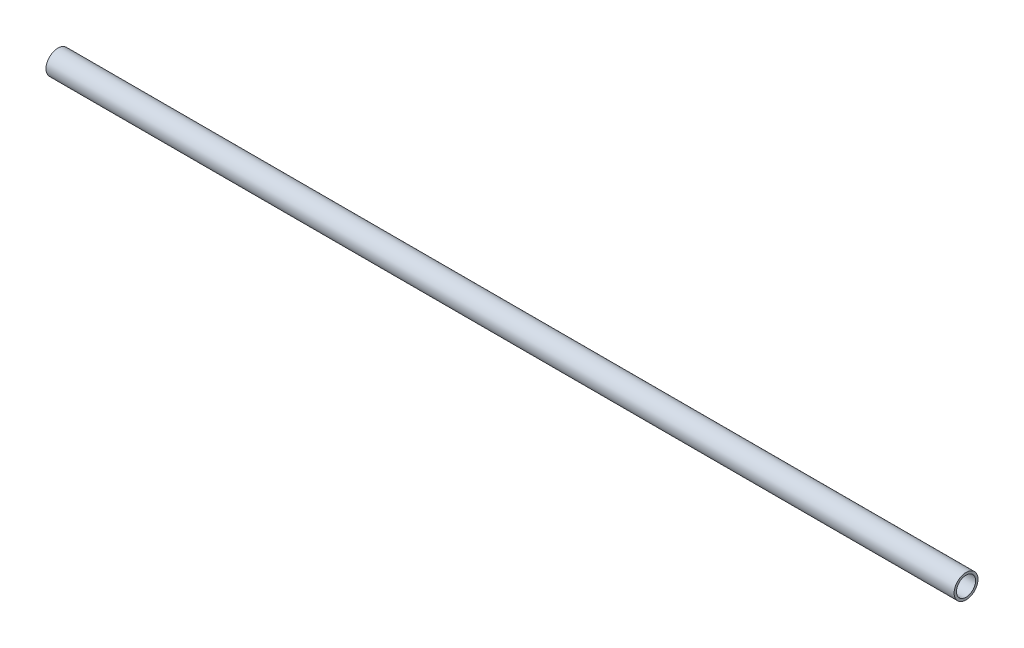
SolidWorks part; units mm, degrees
ref_plane "Front Plane" through (0, 0, 0) normal (0, 0, 1) x (1, 0, 0)
ref_plane "Top Plane" through (0, 0, 0) normal (0, 1, 0) x (1, 0, 0)
ref_plane "Right Plane" through (0, 0, 0) normal (1, 0, 0) x (0, 0, -1)
sketch "Sketch1" plane through (0, 0, 0) normal (1, 0, 0) x (0, 0, -1)
  circle A0 centre (0, 0) radius 2.5
  circle A1 centre (0, 0) radius 2
  dimension "D1" = 5
  dimension "D2" = 4
extrude "Boss-Extrude1" add sketch "Sketch1" along normal mid plane 190
